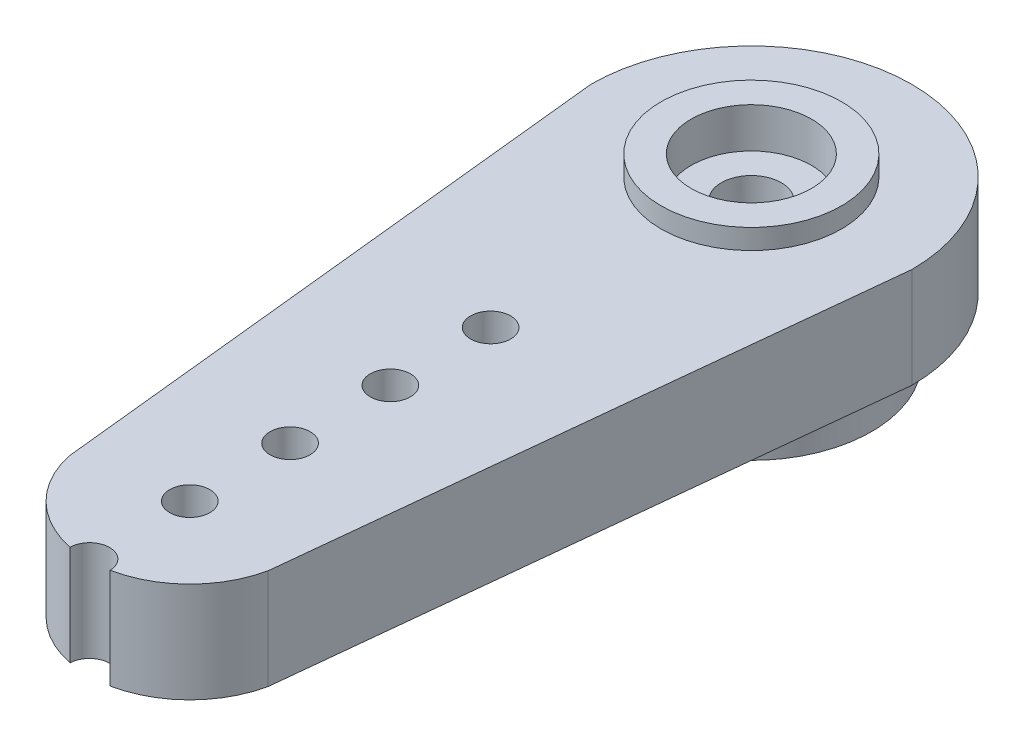
SolidWorks part; units mm, degrees
material "ABS"
ref_plane "Front Plane" through (0, 0, 0) normal (0, 0, 1) x (1, 0, 0)
ref_plane "Top Plane" through (0, 0, 0) normal (0, 1, 0) x (1, 0, 0)
ref_plane "Right Plane" through (0, 0, 0) normal (1, 0, 0) x (0, 0, -1)
sketch "Sketch1" plane through (0, 0, 0) normal (0, 1, 0) x (1, 0, 0)
  circle A0 centre (0, 0) radius 6
  dimension "D1" = 12
extrude "Boss-Extrude1" add sketch "Sketch1" along normal blind 3
sketch "Sketch7" plane through (0, 0, 0) normal (0, -1, 0) x (1, 0, 0)
  line L0 (0, 3.75) -> (0, 3.05) construction
  line L1 (0, 3.05) -> (0.7, 3.6841)
  line L2 (0, 3.05) -> (-0.7, 3.6841)
  line L3 (1.2405, 2.7863) -> (2.1379, 3.0809)
  line L4 (1.2405, 2.7863) -> (0.859, 3.6503)
  line L5 (2.2666, 2.0408) -> (3.2062, 1.9449)
  line L6 (2.2666, 2.0408) -> (2.2694, 2.9853)
  line L7 (2.9007, 0.9425) -> (3.7201, 0.4727)
  line L8 (2.9007, 0.9425) -> (3.2875, 1.8042)
  line L9 (3.0333, -0.3188) -> (3.5907, -1.0813)
  line L10 (3.0333, -0.3188) -> (3.7371, 0.3111)
  line L11 (2.6414, -1.525) -> (2.8405, -2.4483)
  line L12 (2.6414, -1.525) -> (3.5405, -1.2358)
  line L13 (1.7927, -2.4675) -> (1.5991, -3.3919)
  line L14 (1.7927, -2.4675) -> (2.7318, -2.569)
  line L15 (0.6341, -2.9834) -> (0.0813, -3.7491)
  line L16 (0.6341, -2.9834) -> (1.4507, -3.458)
  line L17 (-0.6341, -2.9834) -> (-1.4507, -3.458)
  line L18 (-0.6341, -2.9834) -> (-0.0813, -3.7491)
  line L19 (-1.7927, -2.4675) -> (-2.7318, -2.569)
  line L20 (-1.7927, -2.4675) -> (-1.5991, -3.3919)
  line L21 (-2.6414, -1.525) -> (-3.5405, -1.2358)
  line L22 (-2.6414, -1.525) -> (-2.8405, -2.4483)
  line L23 (-3.0333, -0.3188) -> (-3.7371, 0.3111)
  line L24 (-3.0333, -0.3188) -> (-3.5907, -1.0813)
  line L25 (-2.9007, 0.9425) -> (-3.2875, 1.8042)
  line L26 (-2.9007, 0.9425) -> (-3.7201, 0.4727)
  line L27 (-2.2666, 2.0408) -> (-2.2694, 2.9853)
  line L28 (-2.2666, 2.0408) -> (-3.2062, 1.9449)
  line L29 (-1.2405, 2.7863) -> (-0.859, 3.6503)
  line L30 (-1.2405, 2.7863) -> (-2.1379, 3.0809)
  circle A0 centre (0, 0) radius 3.75 construction
  arc A1 (-0.7, 3.6841) -> (0.7, 3.6841) centre (0, 0) cw construction
  arc A2 (0.7, 3.6841) -> (0.9, 3.6404) centre (0, 0) cw
  arc A3 (2.1379, 3.0809) -> (2.3029, 2.9596) centre (0, 0) cw
  arc A4 (3.2062, 1.9449) -> (3.3076, 1.7671) centre (0, 0) cw
  arc A5 (3.7201, 0.4727) -> (3.7403, 0.269) centre (0, 0) cw
  arc A6 (3.5907, -1.0813) -> (3.5264, -1.2756) centre (0, 0) cw
  arc A7 (2.8405, -2.4483) -> (2.7027, -2.5996) centre (0, 0) cw
  arc A8 (1.5991, -3.3919) -> (1.4117, -3.4742) centre (0, 0) cw
  arc A9 (0.0813, -3.7491) -> (-0.1235, -3.748) centre (0, 0) cw
  arc A10 (-1.4507, -3.458) -> (-1.6372, -3.3737) centre (0, 0) cw
  arc A11 (-2.7318, -2.569) -> (-2.8679, -2.4161) centre (0, 0) cw
  arc A12 (-3.5405, -1.2358) -> (-3.6027, -1.0408) centre (0, 0) cw
  arc A13 (-3.7371, 0.3111) -> (-3.7145, 0.5145) centre (0, 0) cw
  arc A14 (-3.2875, 1.8042) -> (-3.1841, 1.9809) centre (0, 0) cw
  arc A15 (-2.2694, 2.9853) -> (-2.1031, 3.1047) centre (0, 0) cw
  arc A16 (-0.859, 3.6503) -> (-0.6585, 3.6917) centre (0, 0) cw
  point P64 (0, 0)
extrude "Cut-Extrude4" cut sketch "Sketch7" against normal through all
sketch "Sketch2" plane through (0, 3, 0) normal (0, 1, 0) x (1, 0, 0)
  line L0 (8, 0) -> (3.5, -43)
  line L1 (-8, 0) -> (-3.5, -43)
  arc A0 (8, 0) -> (-8, 0) centre (0, 0) ccw
  arc A1 (-3.5, -43) -> (3.5, -43) centre (0, -43) ccw
  dimension "D1" = 16
  dimension "D2" = 7
  dimension "D3" = 43
extrude "Boss-Extrude2" add sketch "Sketch2" along normal blind 5
sketch "Sketch3" plane through (0, 8, 0) normal (0, 1, 0) x (1, 0, 0)
  circle A0 centre (0, 0) radius 4.5
  dimension "D1" = 9
extrude "Boss-Extrude3" add sketch "Sketch3" along normal blind 1
sketch "Sketch4" plane through (0, 9, 0) normal (0, 1, 0) x (1, 0, 0)
  circle A0 centre (0, 0) radius 3
  dimension "D1" = 6
extrude "Cut-Extrude1" cut sketch "Sketch4" against normal blind 2
sketch "Sketch5" plane through (0, 7, 0) normal (0, 1, 0) x (1, 0, 0)
  circle A0 centre (0, 0) radius 1.5
  dimension "D1" = 3
extrude "Cut-Extrude2" cut sketch "Sketch5" against normal through all
sketch "Sketch6" plane through (0, 8, 0) normal (0, 1, 0) x (1, 0, 0)
  line L0 (0, -4.5) -> (0, -18.9486) construction
  circle A0 centre (0, -13) radius 1
  circle A1 centre (0, 0) radius 3 construction
  circle A3 centre (0, 0) radius 4.5 construction
  circle A4 centre (0, 0) radius 4.5 construction
  circle A5 centre (0, -18) radius 1
  circle A6 centre (0, -23) radius 1
  circle A7 centre (0, -28) radius 1
  circle A8 centre (0, -33) radius 1
  circle A9 centre (0, -38) radius 1
  circle A10 centre (0, -43) radius 1
  dimension "D1" = 2
  dimension "D2" = 13
  dimension "D3" = 7
extrude "Cut-Extrude3" cut sketch "Sketch6" against normal blind 10
sketch "Sketch8" plane through (0, 3, 0) normal (0, -1, 0) x (1, 0, 0)
  line L30 (-0.859, 3.6503) -> (-1.2405, 2.7863)
  line L31 (-1.2405, 2.7863) -> (-2.1379, 3.0809)
  line L32 (-2.2694, 2.9853) -> (-2.2666, 2.0408)
  line L33 (-2.2666, 2.0408) -> (-3.2062, 1.9449)
  line L34 (-3.2875, 1.8042) -> (-2.9007, 0.9425)
  line L35 (-2.9007, 0.9425) -> (-3.7201, 0.4727)
  line L36 (-3.7371, 0.3111) -> (-3.0333, -0.3188)
  line L37 (-3.0333, -0.3188) -> (-3.5907, -1.0813)
  line L38 (-3.5405, -1.2358) -> (-2.6414, -1.525)
  line L39 (-2.6414, -1.525) -> (-2.8405, -2.4483)
  line L40 (-2.7318, -2.569) -> (-1.7927, -2.4675)
  line L41 (-1.7927, -2.4675) -> (-1.5991, -3.3919)
  line L42 (-1.4507, -3.458) -> (-0.6341, -2.9834)
  line L43 (-0.6341, -2.9834) -> (-0.0813, -3.7491)
  line L44 (0.0813, -3.7491) -> (0.6341, -2.9834)
  line L45 (0.6341, -2.9834) -> (1.4507, -3.458)
  line L46 (1.5991, -3.3919) -> (1.7927, -2.4675)
  line L47 (1.7927, -2.4675) -> (2.7318, -2.569)
  line L48 (2.8405, -2.4483) -> (2.6414, -1.525)
  line L49 (2.6414, -1.525) -> (3.5405, -1.2358)
  line L50 (3.5907, -1.0813) -> (3.0333, -0.3188)
  line L51 (3.0333, -0.3188) -> (3.7371, 0.3111)
  line L52 (3.7201, 0.4727) -> (2.9007, 0.9425)
  line L53 (2.9007, 0.9425) -> (3.2875, 1.8042)
  line L54 (3.2062, 1.9449) -> (2.2666, 2.0408)
  line L55 (2.2666, 2.0408) -> (2.2694, 2.9853)
  line L56 (2.1379, 3.0809) -> (1.2405, 2.7863)
  line L57 (1.2405, 2.7863) -> (0.859, 3.6503)
  line L58 (0.7, 3.6841) -> (0, 3.05)
  line L59 (0, 3.05) -> (-0.7, 3.6841)
  line L60 (-0.859, 3.6503) -> (-1.2405, 2.7863)
  line L61 (-1.2405, 2.7863) -> (-2.1379, 3.0809)
  line L62 (-2.2694, 2.9853) -> (-2.2666, 2.0408)
  line L63 (-2.2666, 2.0408) -> (-3.2062, 1.9449)
  line L64 (-3.2875, 1.8042) -> (-2.9007, 0.9425)
  line L65 (-2.9007, 0.9425) -> (-3.7201, 0.4727)
  line L66 (-3.7371, 0.3111) -> (-3.0333, -0.3188)
  line L67 (-3.0333, -0.3188) -> (-3.5907, -1.0813)
  line L68 (-3.5405, -1.2358) -> (-2.6414, -1.525)
  line L69 (-2.6414, -1.525) -> (-2.8405, -2.4483)
  line L70 (-2.7318, -2.569) -> (-1.7927, -2.4675)
  line L71 (-1.7927, -2.4675) -> (-1.5991, -3.3919)
  line L72 (-1.4507, -3.458) -> (-0.6341, -2.9834)
  line L73 (-0.6341, -2.9834) -> (-0.0813, -3.7491)
  line L74 (0.0813, -3.7491) -> (0.6341, -2.9834)
  line L75 (0.6341, -2.9834) -> (1.4507, -3.458)
  line L76 (1.5991, -3.3919) -> (1.7927, -2.4675)
  line L77 (1.7927, -2.4675) -> (2.7318, -2.569)
  line L78 (2.8405, -2.4483) -> (2.6414, -1.525)
  line L79 (2.6414, -1.525) -> (3.5405, -1.2358)
  line L80 (3.5907, -1.0813) -> (3.0333, -0.3188)
  line L81 (3.0333, -0.3188) -> (3.7371, 0.3111)
  line L82 (3.7201, 0.4727) -> (2.9007, 0.9425)
  line L83 (2.9007, 0.9425) -> (3.2875, 1.8042)
  line L84 (3.2062, 1.9449) -> (2.2666, 2.0408)
  line L85 (2.2666, 2.0408) -> (2.2694, 2.9853)
  line L86 (2.1379, 3.0809) -> (1.2405, 2.7863)
  line L87 (1.2405, 2.7863) -> (0.859, 3.6503)
  line L88 (0.7, 3.6841) -> (0, 3.05)
  line L89 (0, 3.05) -> (-0.7, 3.6841)
  circle A0 centre (0, 0) radius 1.5 construction
  circle A1 centre (0, 0) radius 1.5
  arc A15 (-0.7, 3.6841) -> (-0.859, 3.6503) centre (0, 0) ccw
  arc A16 (-2.1379, 3.0809) -> (-2.2694, 2.9853) centre (0, 0) ccw
  arc A17 (-3.2062, 1.9449) -> (-3.2875, 1.8042) centre (0, 0) ccw
  arc A18 (-3.7201, 0.4727) -> (-3.7371, 0.3111) centre (0, 0) ccw
  arc A19 (-3.5907, -1.0813) -> (-3.5405, -1.2358) centre (0, 0) ccw
  arc A20 (-2.8405, -2.4483) -> (-2.7318, -2.569) centre (0, 0) ccw
  arc A21 (-1.5991, -3.3919) -> (-1.4507, -3.458) centre (0, 0) ccw
  arc A22 (-0.0813, -3.7491) -> (0.0813, -3.7491) centre (0, 0) ccw
  arc A23 (1.4507, -3.458) -> (1.5991, -3.3919) centre (0, 0) ccw
  arc A24 (2.7318, -2.569) -> (2.8405, -2.4483) centre (0, 0) ccw
  arc A25 (3.5405, -1.2358) -> (3.5907, -1.0813) centre (0, 0) ccw
  arc A26 (3.7371, 0.3111) -> (3.7201, 0.4727) centre (0, 0) ccw
  arc A27 (3.2875, 1.8042) -> (3.2062, 1.9449) centre (0, 0) ccw
  arc A28 (2.2694, 2.9853) -> (2.1379, 3.0809) centre (0, 0) ccw
  arc A29 (0.859, 3.6503) -> (0.7, 3.6841) centre (0, 0) ccw
  arc A30 (-0.7, 3.6841) -> (-0.859, 3.6503) centre (0, 0) ccw
  arc A31 (-2.1379, 3.0809) -> (-2.2694, 2.9853) centre (0, 0) ccw
  arc A32 (-3.2062, 1.9449) -> (-3.2875, 1.8042) centre (0, 0) ccw
  arc A33 (-3.7201, 0.4727) -> (-3.7371, 0.3111) centre (0, 0) ccw
  arc A34 (-3.5907, -1.0813) -> (-3.5405, -1.2358) centre (0, 0) ccw
  arc A35 (-2.8405, -2.4483) -> (-2.7318, -2.569) centre (0, 0) ccw
  arc A36 (-1.5991, -3.3919) -> (-1.4507, -3.458) centre (0, 0) ccw
  arc A37 (-0.0813, -3.7491) -> (0.0813, -3.7491) centre (0, 0) ccw
  arc A38 (1.4507, -3.458) -> (1.5991, -3.3919) centre (0, 0) ccw
  arc A39 (2.7318, -2.569) -> (2.8405, -2.4483) centre (0, 0) ccw
  arc A40 (3.5405, -1.2358) -> (3.5907, -1.0813) centre (0, 0) ccw
  arc A41 (3.7371, 0.3111) -> (3.7201, 0.4727) centre (0, 0) ccw
  arc A42 (3.2875, 1.8042) -> (3.2062, 1.9449) centre (0, 0) ccw
  arc A43 (2.2694, 2.9853) -> (2.1379, 3.0809) centre (0, 0) ccw
  arc A44 (0.859, 3.6503) -> (0.7, 3.6841) centre (0, 0) ccw
  dimension "D1" = 0
extrude "Cut-Extrude5" cut sketch "Sketch8" against normal blind 2
sketch "Sketch9" plane through (0, 8, 0) normal (0, 1, 0) x (1, 0, 0)
  line L0 (3.5, -43) -> (8, 0) construction
  line L1 (-5.0698, -28) -> (-3.5, -43)
  line L2 (5.0698, -28) -> (3.5, -43)
  arc A0 (5.0698, -28) -> (-5.0698, -28) centre (0, -28) cw
  arc A1 (-3.5, -43) -> (3.5, -43) centre (0, -43) ccw
  circle M1 centre (0, -43) radius 1
  circle M2 centre (0, -38) radius 1
  circle M3 centre (0, -33) radius 1
  arc M10 (-3.5, -43) -> (3.5, -43) centre (0, -43) ccw
  line M11 (3.5, -43) -> (8, 0)
extrude "Cut-Extrude6" cut sketch "Sketch9" against normal blind 10 contours A0 L1 M3 M10 M11 M1 M2
